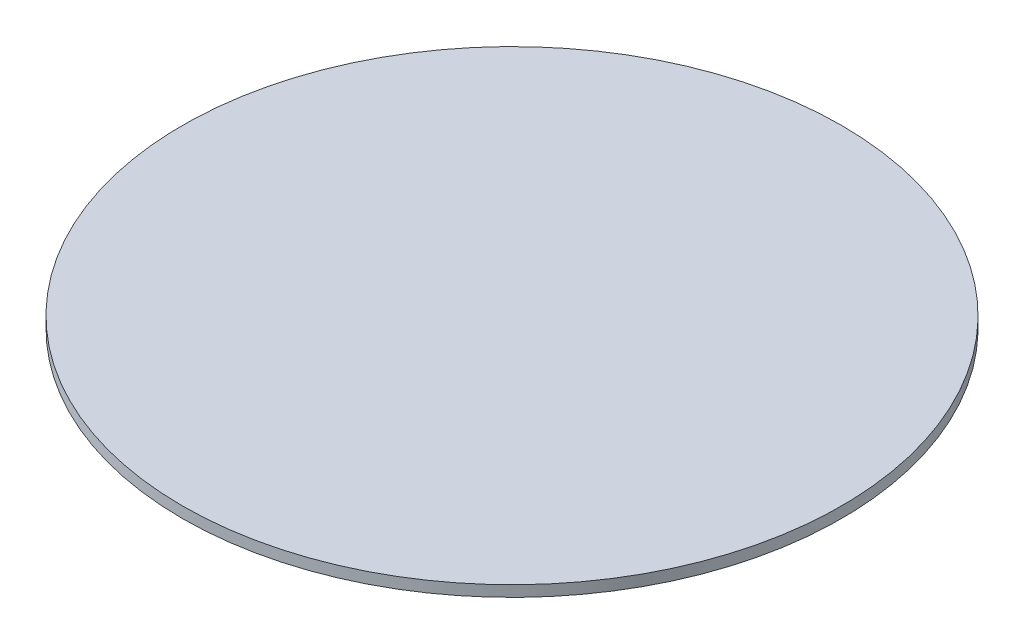
SolidWorks part; units mm, degrees
ref_plane "Front Plane" through (0, 0, 0) normal (0, 0, 1) x (1, 0, 0)
ref_plane "Top Plane" through (0, 0, 0) normal (0, 1, 0) x (1, 0, 0)
ref_plane "Right Plane" through (0, 0, 0) normal (1, 0, 0) x (0, 0, -1)
sketch "Sketch2" plane through (0, 0, 0) normal (0, 1, 0) x (1, 0, 0)
  circle A0 centre (0, 0) radius 9
  dimension "D1" = 18
extrude "Boss-Extrude1" add sketch "Sketch2" along normal blind 0.3
